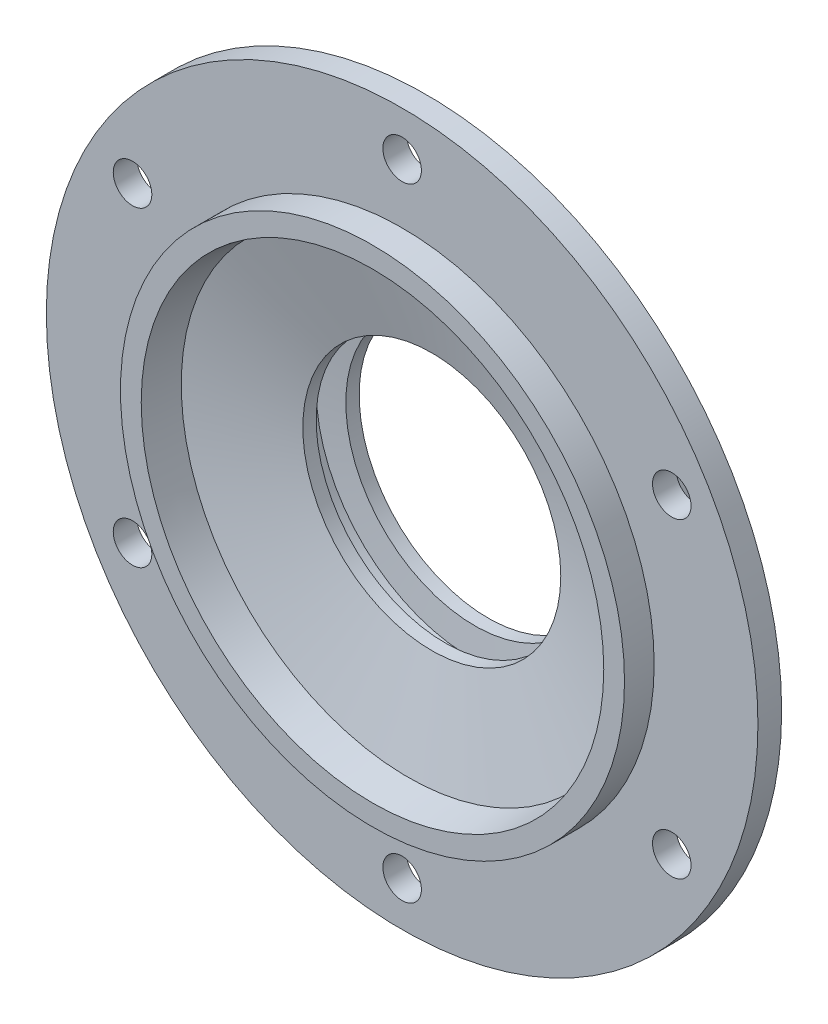
SolidWorks part; units mm, degrees
ref_plane "前视基准面" through (0, 0, 0) normal (0, 0, 1) x (1, 0, 0)
ref_plane "上视基准面" through (0, 0, 0) normal (0, 1, 0) x (1, 0, 0)
ref_plane "右视基准面" through (0, 0, 0) normal (1, 0, 0) x (0, 0, -1)
sketch "草图1" plane through (0, 0, 0) normal (1, 0, 0) x (0, 0, -1)
  line L0 (-1000, 0) -> (49000, 0) construction
  line L1 (-9.5, 43.5) -> (-5, 43.5)
  line L2 (-5, 43.5) -> (-4, 52.5)
  line L3 (-4, 52.5) -> (4, 52.5)
  line L4 (4, 52.5) -> (5, 43.5)
  line L5 (5, 43.5) -> (9.5, 43.5)
  line L6 (0, -1000) -> (0, 49000) construction
  line L7 (9.5, 43.5) -> (9.5, 63)
  line L8 (9.5, 63) -> (2.5, 63)
  line L9 (2.5, 63) -> (2.5, 85)
  line L10 (2.5, 85) -> (-11.5, 85)
  line L11 (-11.5, 85) -> (-11.5, 120)
  line L12 (-11.5, 120) -> (-19.5, 120)
  line L13 (-19.5, 120) -> (-19.5, 85)
  line L14 (-19.5, 85) -> (-29.5, 85)
  line L15 (-29.5, 85) -> (-29.5, 78)
  line L16 (-29.5, 78) -> (-17.5, 76.5)
  line L17 (-17.5, 76.5) -> (-9.5, 43.5)
  dimension "D1" = 8
  dimension "D2" = 10
  dimension "D3" = 4.5
  dimension "D4" = 4.5
  dimension "D5" = 43.5
  dimension "D6" = 52.5
  dimension "D7" = 63
  dimension "D8" = 85
  dimension "D9" = 120
  dimension "D10" = 14
  dimension "D11" = 8
  dimension "D12" = 10
  dimension "D13" = 85
  dimension "D14" = 78
  dimension "D15" = 39
  dimension "D16" = 76.5
  dimension "D17" = 12
revolve "旋转1" add sketch "草图1" angle 360 about L0
sketch "草图2" plane through (0, 0, 11.5) normal (0, 0, -1) x (-1, 0, 0)
  line L0 (0, -1000) -> (0, 49000) construction
  circle A0 centre (0, 105) radius 6.5
  dimension "D1" = 13
  dimension "D2" = 105
extrude "切除-拉伸1" cut sketch "草图2" against normal through all
pattern_circular "阵列(圆周)1" count 6 over 360 about axis through (0, 0, 0) along (0, 0, 1) of "切除-拉伸1"
